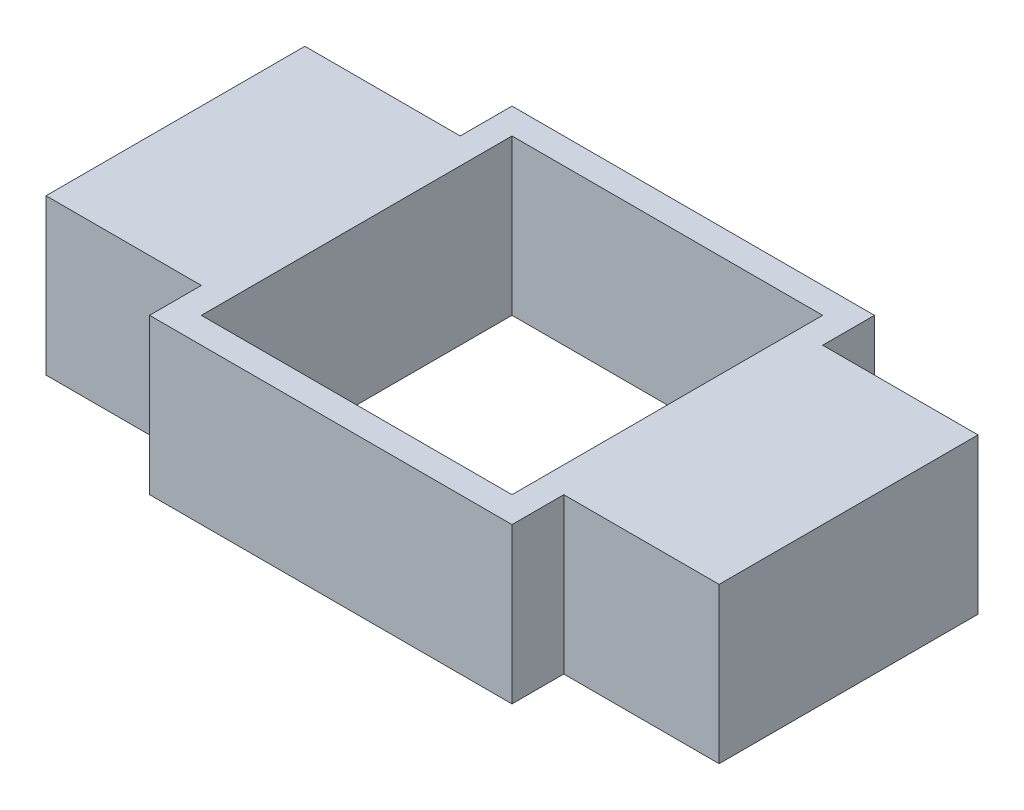
SolidWorks part; units mm, degrees
ref_plane "Plan de face" through (0, 0, 0) normal (0, 0, 1) x (1, 0, 0)
ref_plane "Plan de dessus" through (0, 0, 0) normal (0, 1, 0) x (1, 0, 0)
ref_plane "Plan de droite" through (0, 0, 0) normal (1, 0, 0) x (0, 0, -1)
sketch "Sketch1" plane through (0, 0, 0) normal (0, 1, 0) x (1, 0, 0)
  line L1 (3.5, -3.5) -> (-3.5, -3.5)
  line L2 (3.5, -3.5) -> (3.5, 3.5)
  line L3 (3.5, 3.5) -> (-3.5, 3.5)
  line L4 (-3.5, -3.5) -> (-3.5, 3.5)
  line L5 (3.5, -3.5) -> (-3.5, 3.5) construction
  line L6 (3.5, 3.5) -> (-3.5, -3.5) construction
  point P0 (0, 0)
  dimension "D1" = 7
  dimension "D2" = 7
extrude "Boss-Extrude1" add sketch "Sketch1" along normal blind 3
sketch "Sketch4" plane through (0, 3, 0) normal (0, 1, 0) x (1, 0, 0)
  line L0 (-3.5, 3.5) -> (-3.5, -3.5) construction
  line L1 (-3.5, 2.5) -> (-6.5, 2.5)
  line L2 (-3.5, 2.5) -> (-3.5, -2.5)
  line L3 (-3.5, -2.5) -> (-6.5, -2.5)
  line L4 (-6.5, 2.5) -> (-6.5, -2.5)
  line L5 (3.5, 3.5) -> (-3.5, 3.5) construction
  line L7 (3.5, -3.5) -> (3.5, 3.5) construction
  line L8 (3.5, 2.5) -> (6.5, 2.5)
  line L9 (3.5, 2.5) -> (3.5, -2.5)
  line L10 (3.5, -2.5) -> (6.5, -2.5)
  line L11 (6.5, 2.5) -> (6.5, -2.5)
  dimension "D1" = 5
  dimension "D2" = 1
  dimension "D3" = 3
  dimension "D4" = 5
  dimension "D5" = 3
extrude "Boss-Extrude2" add sketch "Sketch4" against normal blind 3
sketch "Sketch5" plane through (0, 3, 0) normal (0, 1, 0) x (1, 0, 0)
  line L1 (3, -3) -> (-3, -3)
  line L2 (3, -3) -> (3, 3)
  line L3 (3, 3) -> (-3, 3)
  line L4 (-3, -3) -> (-3, 3)
  line L5 (3, -3) -> (-3, 3) construction
  line L6 (3, 3) -> (-3, -3) construction
  point P0 (0, 0)
  dimension "D1" = 6
  dimension "D2" = 6
extrude "Cut-Extrude1" cut sketch "Sketch5" against normal blind 10
